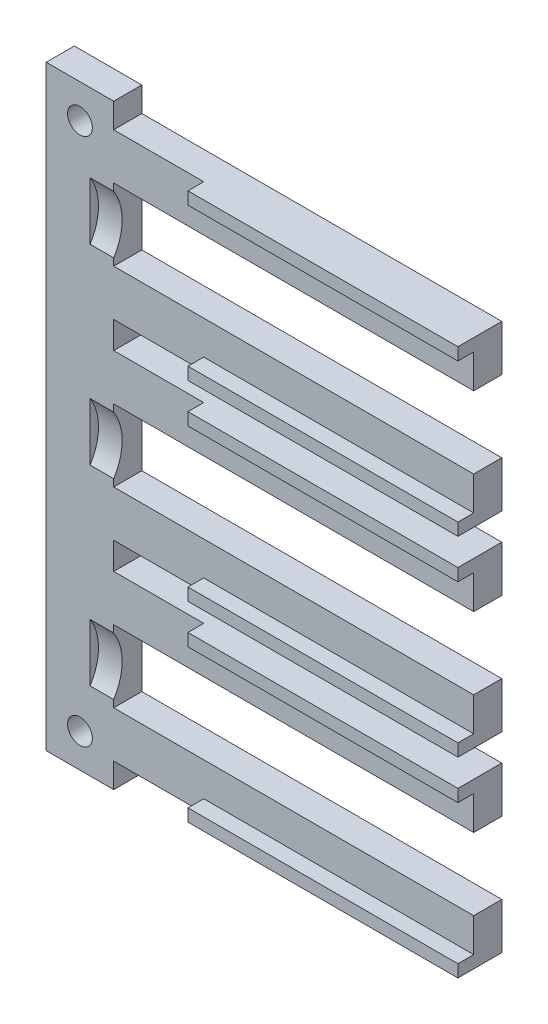
SolidWorks part; units mm, degrees
other "Spring Front Grip Acetal Guide Comb"
ref_plane "Front Plane" through (0, 0, 0) normal (0, 0, 1) x (1, 0, 0)
ref_plane "Top Plane" through (0, 0, 0) normal (0, 1, 0) x (1, 0, 0)
ref_plane "Right Plane" through (0, 0, 0) normal (1, 0, 0) x (0, 0, -1)
sketch3d "Front Grip Acetal Guide Comb sketch datum points"
  point P0 (-66.2917, -55.5, 8.5)
  point P1 (-56.2917, -55.5, 8.5)
  point P2 (-66.2917, -45.5, 8.5)
ref_plane "Front Grip Acetal Guide Comb sketch plane" through (0, 0, 8.5) normal (0, 0, 1) x (1, 0, 0)
sketch "Front Grip Acetal Guide Comb sketch" plane through (0, 0, 8.5) normal (0, 0, 1) x (1, 0, 0)
  line L0 (-66.2917, -55.5) -> (-60.2917, -55.5)
  line L1 (-60.2917, -55.5) -> (-60.2917, -2.5)
  line L2 (-60.2917, -2.5) -> (-66.2917, -2.5)
  line L3 (-66.2917, -2.5) -> (-66.2917, -55.5)
extrude "Front Grip Acetal Guide Comb" add sketch "Front Grip Acetal Guide Comb sketch" along normal blind 2.5 separate body
sketch3d "Grip Guide Ledge 1 Lower sketch datum points"
  point P0 (-60.3917, -8.8, 8.5)
  point P1 (-50.3917, -8.8, 8.5)
  point P2 (-60.3917, 1.2, 8.5)
ref_plane "Grip Guide Ledge 1 Lower sketch plane" through (0, 0, 8.5) normal (0, 0, 1) x (1, 0, 0)
sketch "Grip Guide Ledge 1 Lower sketch" plane through (0, 0, 8.5) normal (0, 0, 1) x (1, 0, 0)
  line L0 (-60.3917, -8.8) -> (-28.2917, -8.8)
  line L1 (-28.2917, -8.8) -> (-28.2917, -4.7)
  line L2 (-28.2917, -4.7) -> (-60.3917, -4.7)
  line L3 (-60.3917, -4.7) -> (-60.3917, -8.8)
extrude "Grip Guide Ledge 1 Lower" add sketch "Grip Guide Ledge 1 Lower sketch" along normal blind 2.5
sketch3d "Grip Guide Ledge 1 Upper sketch datum points"
  point P0 (-60.3917, -19.3, 8.5)
  point P1 (-50.3917, -19.3, 8.5)
  point P2 (-60.3917, -9.3, 8.5)
ref_plane "Grip Guide Ledge 1 Upper sketch plane" through (0, 0, 8.5) normal (0, 0, 1) x (1, 0, 0)
sketch "Grip Guide Ledge 1 Upper sketch" plane through (0, 0, 8.5) normal (0, 0, 1) x (1, 0, 0)
  line L0 (-60.3917, -19.3) -> (-28.2917, -19.3)
  line L1 (-28.2917, -19.3) -> (-28.2917, -15.2)
  line L2 (-28.2917, -15.2) -> (-60.3917, -15.2)
  line L3 (-60.3917, -15.2) -> (-60.3917, -19.3)
extrude "Grip Guide Ledge 1 Upper" add sketch "Grip Guide Ledge 1 Upper sketch" along normal blind 2.5
sketch3d "Grip Guide Fence 1 Lower sketch datum points"
  point P0 (-52.2917, -5.8, 10.9)
  point P1 (-42.2917, -5.8, 10.9)
  point P2 (-52.2917, 4.2, 10.9)
ref_plane "Grip Guide Fence 1 Lower sketch plane" through (0, 0, 10.9) normal (0, 0, 1) x (1, 0, 0)
sketch "Grip Guide Fence 1 Lower sketch" plane through (0, 0, 10.9) normal (0, 0, 1) x (1, 0, 0)
  line L0 (-52.2917, -5.8) -> (-28.2917, -5.8)
  line L1 (-28.2917, -5.8) -> (-28.2917, -4.7)
  line L2 (-28.2917, -4.7) -> (-52.2917, -4.7)
  line L3 (-52.2917, -4.7) -> (-52.2917, -5.8)
extrude "Grip Guide Fence 1 Lower" add sketch "Grip Guide Fence 1 Lower sketch" along normal blind 1.5
sketch3d "Grip Guide Fence 1 Upper sketch datum points"
  point P0 (-52.2917, -19.3, 10.9)
  point P1 (-42.2917, -19.3, 10.9)
  point P2 (-52.2917, -9.3, 10.9)
ref_plane "Grip Guide Fence 1 Upper sketch plane" through (0, 0, 10.9) normal (0, 0, 1) x (1, 0, 0)
sketch "Grip Guide Fence 1 Upper sketch" plane through (0, 0, 10.9) normal (0, 0, 1) x (1, 0, 0)
  line L0 (-52.2917, -19.3) -> (-28.2917, -19.3)
  line L1 (-28.2917, -19.3) -> (-28.2917, -18.2)
  line L2 (-28.2917, -18.2) -> (-52.2917, -18.2)
  line L3 (-52.2917, -18.2) -> (-52.2917, -19.3)
extrude "Grip Guide Fence 1 Upper" add sketch "Grip Guide Fence 1 Upper sketch" along normal blind 1.5
sketch3d "Grip Guide Ledge 2 Lower sketch datum points"
  point P0 (-60.3917, -25.8, 8.5)
  point P1 (-50.3917, -25.8, 8.5)
  point P2 (-60.3917, -15.8, 8.5)
ref_plane "Grip Guide Ledge 2 Lower sketch plane" through (0, 0, 8.5) normal (0, 0, 1) x (1, 0, 0)
sketch "Grip Guide Ledge 2 Lower sketch" plane through (0, 0, 8.5) normal (0, 0, 1) x (1, 0, 0)
  line L0 (-60.3917, -25.8) -> (-28.2917, -25.8)
  line L1 (-28.2917, -25.8) -> (-28.2917, -21.7)
  line L2 (-28.2917, -21.7) -> (-60.3917, -21.7)
  line L3 (-60.3917, -21.7) -> (-60.3917, -25.8)
extrude "Grip Guide Ledge 2 Lower" add sketch "Grip Guide Ledge 2 Lower sketch" along normal blind 2.5
sketch3d "Grip Guide Ledge 2 Upper sketch datum points"
  point P0 (-60.3917, -36.3, 8.5)
  point P1 (-50.3917, -36.3, 8.5)
  point P2 (-60.3917, -26.3, 8.5)
ref_plane "Grip Guide Ledge 2 Upper sketch plane" through (0, 0, 8.5) normal (0, 0, 1) x (1, 0, 0)
sketch "Grip Guide Ledge 2 Upper sketch" plane through (0, 0, 8.5) normal (0, 0, 1) x (1, 0, 0)
  line L0 (-60.3917, -36.3) -> (-28.2917, -36.3)
  line L1 (-28.2917, -36.3) -> (-28.2917, -32.2)
  line L2 (-28.2917, -32.2) -> (-60.3917, -32.2)
  line L3 (-60.3917, -32.2) -> (-60.3917, -36.3)
extrude "Grip Guide Ledge 2 Upper" add sketch "Grip Guide Ledge 2 Upper sketch" along normal blind 2.5
sketch3d "Grip Guide Fence 2 Lower sketch datum points"
  point P0 (-52.2917, -22.8, 10.9)
  point P1 (-42.2917, -22.8, 10.9)
  point P2 (-52.2917, -12.8, 10.9)
ref_plane "Grip Guide Fence 2 Lower sketch plane" through (0, 0, 10.9) normal (0, 0, 1) x (1, 0, 0)
sketch "Grip Guide Fence 2 Lower sketch" plane through (0, 0, 10.9) normal (0, 0, 1) x (1, 0, 0)
  line L0 (-52.2917, -22.8) -> (-28.2917, -22.8)
  line L1 (-28.2917, -22.8) -> (-28.2917, -21.7)
  line L2 (-28.2917, -21.7) -> (-52.2917, -21.7)
  line L3 (-52.2917, -21.7) -> (-52.2917, -22.8)
extrude "Grip Guide Fence 2 Lower" add sketch "Grip Guide Fence 2 Lower sketch" along normal blind 1.5
sketch3d "Grip Guide Fence 2 Upper sketch datum points"
  point P0 (-52.2917, -36.3, 10.9)
  point P1 (-42.2917, -36.3, 10.9)
  point P2 (-52.2917, -26.3, 10.9)
ref_plane "Grip Guide Fence 2 Upper sketch plane" through (0, 0, 10.9) normal (0, 0, 1) x (1, 0, 0)
sketch "Grip Guide Fence 2 Upper sketch" plane through (0, 0, 10.9) normal (0, 0, 1) x (1, 0, 0)
  line L0 (-52.2917, -36.3) -> (-28.2917, -36.3)
  line L1 (-28.2917, -36.3) -> (-28.2917, -35.2)
  line L2 (-28.2917, -35.2) -> (-52.2917, -35.2)
  line L3 (-52.2917, -35.2) -> (-52.2917, -36.3)
extrude "Grip Guide Fence 2 Upper" add sketch "Grip Guide Fence 2 Upper sketch" along normal blind 1.5
sketch3d "Grip Guide Ledge 3 Lower sketch datum points"
  point P0 (-60.3917, -42.8, 8.5)
  point P1 (-50.3917, -42.8, 8.5)
  point P2 (-60.3917, -32.8, 8.5)
ref_plane "Grip Guide Ledge 3 Lower sketch plane" through (0, 0, 8.5) normal (0, 0, 1) x (1, 0, 0)
sketch "Grip Guide Ledge 3 Lower sketch" plane through (0, 0, 8.5) normal (0, 0, 1) x (1, 0, 0)
  line L0 (-60.3917, -42.8) -> (-28.2917, -42.8)
  line L1 (-28.2917, -42.8) -> (-28.2917, -38.7)
  line L2 (-28.2917, -38.7) -> (-60.3917, -38.7)
  line L3 (-60.3917, -38.7) -> (-60.3917, -42.8)
extrude "Grip Guide Ledge 3 Lower" add sketch "Grip Guide Ledge 3 Lower sketch" along normal blind 2.5
sketch3d "Grip Guide Ledge 3 Upper sketch datum points"
  point P0 (-60.3917, -53.3, 8.5)
  point P1 (-50.3917, -53.3, 8.5)
  point P2 (-60.3917, -43.3, 8.5)
ref_plane "Grip Guide Ledge 3 Upper sketch plane" through (0, 0, 8.5) normal (0, 0, 1) x (1, 0, 0)
sketch "Grip Guide Ledge 3 Upper sketch" plane through (0, 0, 8.5) normal (0, 0, 1) x (1, 0, 0)
  line L0 (-60.3917, -53.3) -> (-28.2917, -53.3)
  line L1 (-28.2917, -53.3) -> (-28.2917, -49.2)
  line L2 (-28.2917, -49.2) -> (-60.3917, -49.2)
  line L3 (-60.3917, -49.2) -> (-60.3917, -53.3)
extrude "Grip Guide Ledge 3 Upper" add sketch "Grip Guide Ledge 3 Upper sketch" along normal blind 2.5
sketch3d "Grip Guide Fence 3 Lower sketch datum points"
  point P0 (-52.2917, -39.8, 10.9)
  point P1 (-42.2917, -39.8, 10.9)
  point P2 (-52.2917, -29.8, 10.9)
ref_plane "Grip Guide Fence 3 Lower sketch plane" through (0, 0, 10.9) normal (0, 0, 1) x (1, 0, 0)
sketch "Grip Guide Fence 3 Lower sketch" plane through (0, 0, 10.9) normal (0, 0, 1) x (1, 0, 0)
  line L0 (-52.2917, -39.8) -> (-28.2917, -39.8)
  line L1 (-28.2917, -39.8) -> (-28.2917, -38.7)
  line L2 (-28.2917, -38.7) -> (-52.2917, -38.7)
  line L3 (-52.2917, -38.7) -> (-52.2917, -39.8)
extrude "Grip Guide Fence 3 Lower" add sketch "Grip Guide Fence 3 Lower sketch" along normal blind 1.5
sketch3d "Grip Guide Fence 3 Upper sketch datum points"
  point P0 (-52.2917, -53.3, 10.9)
  point P1 (-42.2917, -53.3, 10.9)
  point P2 (-52.2917, -43.3, 10.9)
ref_plane "Grip Guide Fence 3 Upper sketch plane" through (0, 0, 10.9) normal (0, 0, 1) x (1, 0, 0)
sketch "Grip Guide Fence 3 Upper sketch" plane through (0, 0, 10.9) normal (0, 0, 1) x (1, 0, 0)
  line L0 (-52.2917, -53.3) -> (-28.2917, -53.3)
  line L1 (-28.2917, -53.3) -> (-28.2917, -52.2)
  line L2 (-28.2917, -52.2) -> (-52.2917, -52.2)
  line L3 (-52.2917, -52.2) -> (-52.2917, -53.3)
extrude "Grip Guide Fence 3 Upper" add sketch "Grip Guide Fence 3 Upper sketch" along normal blind 1.5
sketch3d "Front Guide Screw Clearance 1 sketch datum points"
  point P0 (-63.2917, -5.5, 8.4)
  point P1 (-53.2917, -5.5, 8.4)
  point P2 (-63.2917, 4.5, 8.4)
ref_plane "Front Guide Screw Clearance 1 sketch plane" through (0, 0, 8.4) normal (0, 0, 1) x (1, 0, 0)
sketch "Front Guide Screw Clearance 1 sketch" plane through (0, 0, 8.4) normal (0, 0, 1) x (1, 0, 0)
  circle A0 centre (-63.2917, -5.5) radius 1.1
extrude "Front Guide Screw Clearance 1" cut sketch "Front Guide Screw Clearance 1 sketch" along normal blind 2.7
sketch3d "Front Guide Screw Clearance 2 sketch datum points"
  point P0 (-63.2917, -52.5, 8.4)
  point P1 (-53.2917, -52.5, 8.4)
  point P2 (-63.2917, -42.5, 8.4)
ref_plane "Front Guide Screw Clearance 2 sketch plane" through (0, 0, 8.4) normal (0, 0, 1) x (1, 0, 0)
sketch "Front Guide Screw Clearance 2 sketch" plane through (0, 0, 8.4) normal (0, 0, 1) x (1, 0, 0)
  circle A0 centre (-63.2917, -52.5) radius 1.1
extrude "Front Guide Screw Clearance 2" cut sketch "Front Guide Screw Clearance 2 sketch" along normal blind 2.7
sketch3d "Outlet seat clearance 1 sketch datum points"
  point P0 (-62.3917, -12, 15)
  point P1 (-62.3917, -2, 15)
  point P2 (-62.3917, -12, 25)
ref_plane "Outlet seat clearance 1 sketch plane" through (-62.3917, 0, 0) normal (1, 0, 0) x (0, 0, -1)
sketch "Outlet seat clearance 1 sketch" plane through (-62.3917, 0, 0) normal (1, 0, 0) x (0, 0, -1)
  circle A0 centre (-15, -12) radius 4.75
extrude "Outlet seat clearance 1" cut sketch "Outlet seat clearance 1 sketch" along normal blind 2.2
sketch3d "Outlet seat clearance 2 sketch datum points"
  point P0 (-62.3917, -29, 15)
  point P1 (-62.3917, -19, 15)
  point P2 (-62.3917, -29, 25)
ref_plane "Outlet seat clearance 2 sketch plane" through (-62.3917, 0, 0) normal (1, 0, 0) x (0, 0, -1)
sketch "Outlet seat clearance 2 sketch" plane through (-62.3917, 0, 0) normal (1, 0, 0) x (0, 0, -1)
  circle A0 centre (-15, -29) radius 4.75
extrude "Outlet seat clearance 2" cut sketch "Outlet seat clearance 2 sketch" along normal blind 2.2
sketch3d "Outlet seat clearance 3 sketch datum points"
  point P0 (-62.3917, -46, 15)
  point P1 (-62.3917, -36, 15)
  point P2 (-62.3917, -46, 25)
ref_plane "Outlet seat clearance 3 sketch plane" through (-62.3917, 0, 0) normal (1, 0, 0) x (0, 0, -1)
sketch "Outlet seat clearance 3 sketch" plane through (-62.3917, 0, 0) normal (1, 0, 0) x (0, 0, -1)
  circle A0 centre (-15, -46) radius 4.75
extrude "Outlet seat clearance 3" cut sketch "Outlet seat clearance 3 sketch" along normal blind 2.2
